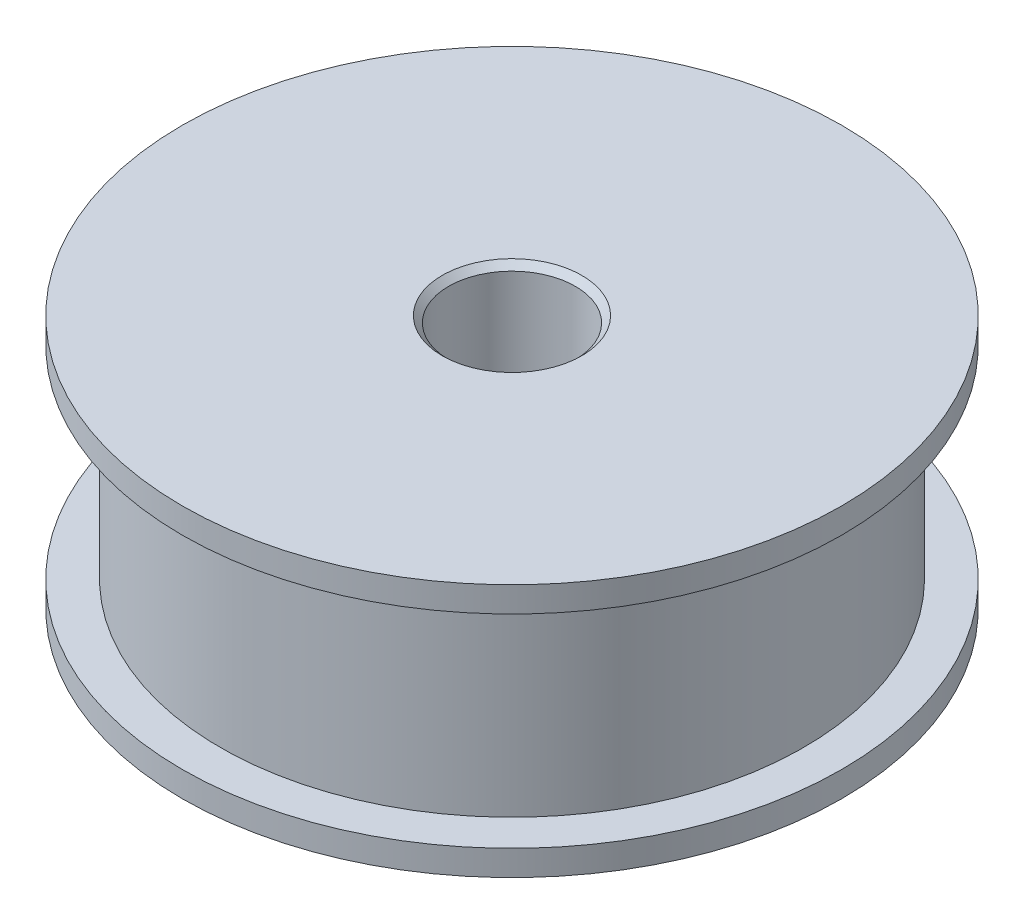
SolidWorks part; units mm, degrees
ref_plane "Front" through (0, 0, 0) normal (0, 0, 1) x (1, 0, 0)
ref_plane "Top" through (0, 0, 0) normal (0, 1, 0) x (1, 0, 0)
ref_plane "Right" through (0, 0, 0) normal (1, 0, 0) x (0, 0, -1)
sketch "草图1" plane through (0, 0, 0) normal (0, 1, 0) x (1, 0, 0)
  circle A0 centre (0, 0) radius 26
  dimension "D1" = 52
extrude "凸台-拉伸1" add sketch "草图1" along normal blind 20
sketch "草图2" plane through (0, 0, 0) normal (0, -1, 0) x (1, 0, 0)
  circle A0 centre (0, 0) radius 26
  circle A1 centre (0, 0) radius 23
  dimension "D1" = 46
extrude "切除-拉伸1" cut sketch "草图2" against normal blind 16 from offset 2 offset against normal yes
sketch "草图3" plane through (0, 0, 0) normal (0, -1, 0) x (1, 0, 0)
  circle A0 centre (0, 0) radius 5
  dimension "D1" = 10
extrude "切除-拉伸2" cut sketch "草图3" against normal through all
chamfer "倒角1" distance 0.5 angle 45 2 edges at (0, 20, -5) (0, 0, -5)
sketch "草图4" plane through (0, 0, 0) normal (0, 0, 1) x (1, 0, 0)
  line L0 (0, 20) -> (0, 0) construction
  line L1 (5.5, 20) -> (-5.5, 20) construction
  circle A0 centre (0, 10) radius 1.25
  dimension "D1" = 2.5
extrude "切除-拉伸3" cut sketch "草图4" against normal through all
cosmetic thread "装饰螺纹线2" parameters "D1"=5, "D2"=3
sketch "草图5" plane through (0, 0, 0) normal (1, 0, 0) x (0, 0, -1)
  line L0 (0, 0) -> (0, 20) construction
  line L1 (-26, 0) -> (26, 0) construction
  line L2 (5.5, 20) -> (-5.5, 20) construction
  circle A0 centre (0, 10) radius 1.25
  point P8 (0, 10)
  dimension "D1" = 2.5
extrude "切除-拉伸4" cut sketch "草图5" against normal through all
cosmetic thread "装饰螺纹线1" parameters "D1"=5, "D2"=3
